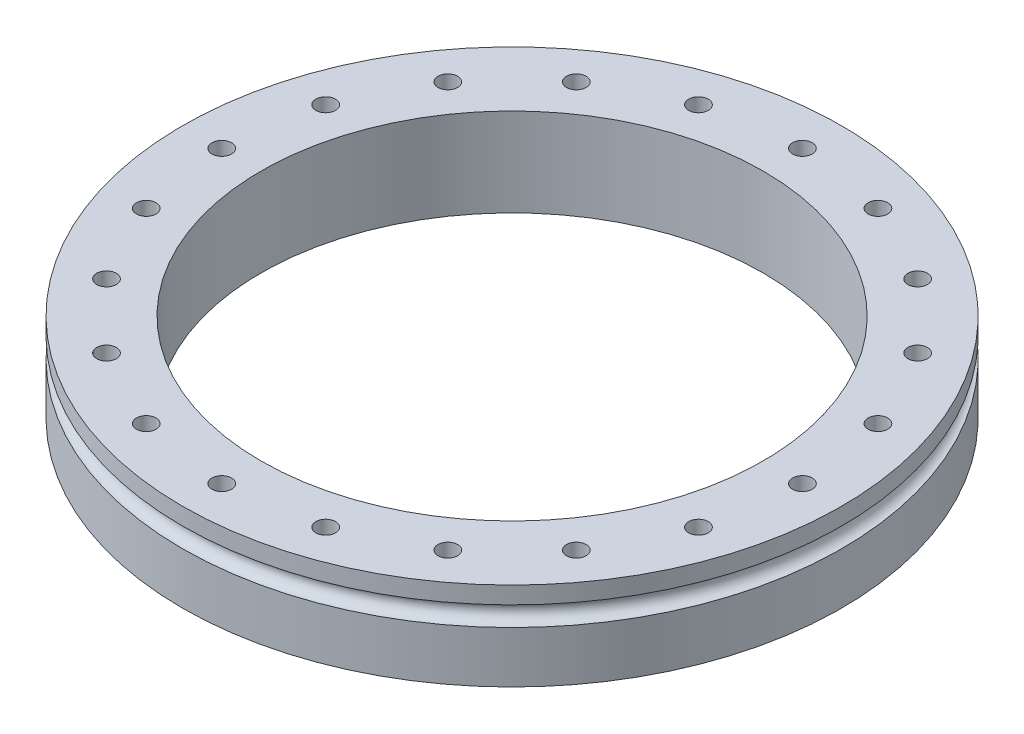
SolidWorks part; units mm, degrees
ref_plane "Plan de face" through (0, 0, 0) normal (0, 0, 1) x (1, 0, 0)
ref_plane "Plan de dessus" through (0, 0, 0) normal (0, 1, 0) x (1, 0, 0)
ref_plane "Plan de droite" through (0, 0, 0) normal (1, 0, 0) x (0, 0, -1)
sketch "Esquisse1" plane through (0, 0, 0) normal (0, 0, 1) x (1, 0, 0)
  line L0 (-256, 27.4194) -> (-256, -16.0215) construction
  line L1 (0, 0) -> (80, 0)
  line L2 (0, 0) -> (0, 90)
  line L3 (0, 90) -> (80, 90)
  line L4 (80, 0) -> (80, 52.5)
  line L5 (80, 72.5) -> (80, 90)
  arc A0 (80, 72.5) -> (80, 52.5) centre (80, 62.5) ccw
  dimension "D4" = 10
  dimension "D1" = 80
  dimension "D2" = 90
  dimension "D3" = 62.5
  dimension "D5" = 256
revolve "Révolution1" add sketch "Esquisse1" angle 360 about L0
sketch "Esquisse2" plane through (0, 0, 0) normal (0, -1, 0) x (1, 0, 0)
  line L0 (0, 0) -> (35.0097, 0) construction
  line L1 (0, 0) -> (80, 0) construction
  circle A0 centre (-256, 0) radius 336 construction
  circle A1 centre (40, 0) radius 10
  dimension "D2" = 20
  dimension "D1" = 40
extrude "Enlèv. mat.-Extru.1" cut sketch "Esquisse2" against normal through all
pattern_circular "Répétition circulaire1" count 20 over 360 about axis through (-256, 0, 0) along (0, 1, 0) of "Enlèv. mat.-Extru.1"
